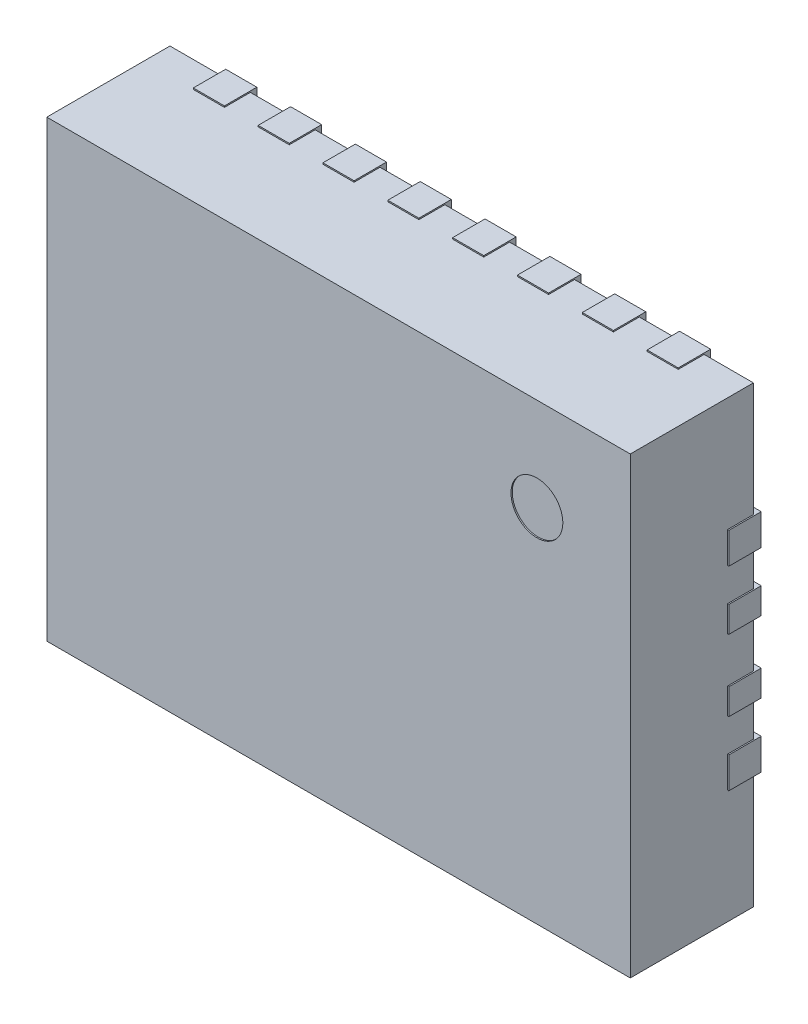
SolidWorks part; units mm, degrees
ref_plane "Front Plane" through (0, 0, 0) normal (0, 0, 1) x (1, 0, 0)
ref_plane "Top Plane" through (0, 0, 0) normal (0, 1, 0) x (1, 0, 0)
ref_plane "Right Plane" through (0, 0, 0) normal (1, 0, 0) x (0, 0, -1)
sketch "Sketch1" plane through (0, 0, 0) normal (0, 0, 1) x (1, 0, 0)
  line L1 (-2.25, 1.75) -> (2.25, 1.75)
  line L2 (-2.25, 1.75) -> (-2.25, -1.75)
  line L3 (-2.25, -1.75) -> (2.25, -1.75)
  line L4 (2.25, 1.75) -> (2.25, -1.75)
  line L5 (-2.25, 1.75) -> (2.25, -1.75) construction
  line L6 (-2.25, -1.75) -> (2.25, 1.75) construction
  point P0 (0, 0)
  dimension "D1" = 4.5
  dimension "D2" = 3.5
extrude "Boss-Extrude1" add sketch "Sketch1" along normal blind 0.95 contours L4 L3 L2 L1
sketch "Sketch2" plane through (0, 0, 0.95) normal (0, 0, 1) x (1, 0, 0)
  line L0 (1.53, 1.03) -> (1.53, 1.75) construction
  line L1 (-2.25, 1.75) -> (2.25, 1.75) construction
  line L2 (1.53, 1.03) -> (2.25, 1.03) construction
  line L4 (2.25, 1.75) -> (2.25, -1.75) construction
  circle A0 centre (1.53, 1.03) radius 0.2
  dimension "D1" = 0.4
  dimension "D2" = 0.72
extrude "Cut-Extrude1" cut sketch "Sketch2" against normal blind 0.01
sketch "Sketch3" plane through (0, 0, 0) normal (0, 0, -1) x (-1, 0, 0)
  line L0 (1.525, 0.375) -> (2.26, 0.375)
  line L1 (1.4995, -1.025) -> (-1.4995, -1.025)
  line L2 (1.525, -0.9995) -> (1.525, -0.375)
  line L3 (1.4995, 1.025) -> (-1.4995, 1.025)
  line L4 (-1.525, -0.9995) -> (-1.525, -0.375)
  line L5 (1.525, -1.025) -> (-1.525, 1.025) construction
  line L6 (1.525, 1.025) -> (-1.525, -1.025) construction
  line L7 (2.25, 1.75) -> (2.25, -1.75) construction
  line L8 (2.26, 0.375) -> (2.26, 0.175)
  line L9 (2.26, 0.175) -> (1.87, 0.175)
  line L10 (1.87, 0.175) -> (1.87, -0.175)
  line L11 (1.87, -0.175) -> (2.26, -0.175)
  line L12 (2.26, -0.175) -> (2.26, -0.375)
  line L13 (2.26, -0.375) -> (1.525, -0.375)
  line L14 (1.525, 0.375) -> (1.525, 0.9995)
  line L15 (-1.525, 0.375) -> (-2.26, 0.375)
  line L16 (-2.25, 1.75) -> (-2.25, -1.75) construction
  line L17 (-2.26, 0.375) -> (-2.26, 0.175)
  line L18 (-2.26, 0.175) -> (-1.87, 0.175)
  line L19 (-1.87, 0.175) -> (-1.87, -0.175)
  line L20 (-1.87, -0.175) -> (-2.26, -0.175)
  line L21 (-2.26, -0.175) -> (-2.26, -0.375)
  line L22 (-2.26, -0.375) -> (-1.525, -0.375)
  line L23 (-1.525, 0.375) -> (-1.525, 0.9995)
  line L24 (-1.175, 1.025) -> (-1.525, 0.675)
  arc A0 (-1.4995, -1.025) -> (-1.525, -0.9995) centre (-1.4995, -0.9995) cw
  arc A1 (-1.4995, 1.025) -> (-1.525, 0.9995) centre (-1.4995, 0.9995) ccw
  arc A2 (1.525, 0.9995) -> (1.4995, 1.025) centre (1.4995, 0.9995) ccw
  arc A3 (1.525, -0.9995) -> (1.4995, -1.025) centre (1.4995, -0.9995) cw
  point P0 (0, 0)
  point P28 (1.87, 0)
  point P30 (2.26, -0.275)
  point P31 (2.26, 0.275)
  point P41 (-1.87, 0)
  line M2 (-2.25, 1.75) -> (-2.25, -1.75)
  line M4 (2.25, -1.75) -> (2.25, 1.75)
  dimension "D3" = 0.0255
  dimension "D1" = 3.05
  dimension "D2" = 2.05
  dimension "D4" = 0.2
  dimension "D5" = 0.55
  dimension "D6" = 0.38
  dimension "D7" = 0.2
  dimension "D8" = 0.38
  dimension "D9" = 45
  dimension "D10" = 0.35
  dimension "D11" = 0.01
  dimension "D12" = 0.01
extrude "Boss-Extrude2" add sketch "Sketch3" along normal blind 0.05 and the other way blind 0.2 contours A3 L2 L13 L11 L10 L9 L0 L14 A2 L3 L24 L23 L15 L18 L19 L20 L22 L4 A0 L1 M4 M2 | L9 L8 L0 M4 | L13 L12 L11 M4 | L21 L22 L20 M2 | L17 L18 L15 M2
sketch "Sketch5" plane through (0, 0, 0) normal (0, 0, -1) x (-1, 0, 0)
  line L0 (1.97, 0.87) -> (2.25, 0.87)
  line L2 (1.97, 0.63) -> (2.25, 0.63)
  line L6 (2.25, 0.87) -> (2.26, 0.87)
  line L7 (2.26, 0.87) -> (2.26, 0.63)
  line L8 (2.26, 0.63) -> (2.25, 0.63)
  line L9 (2.25, 1.75) -> (2.25, 0.375) construction
  arc A0 (1.97, 0.87) -> (1.97, 0.63) centre (1.97, 0.75) ccw
  point P8 (1.85, 0.75)
  dimension "D2" = 0.01
  dimension "D3" = 0.4
  dimension "D4" = 0.75
  dimension "D1" = 0.24
extrude "Boss-Extrude3" add sketch "Sketch5" along normal blind 0.05 and the other way blind 0.2
pattern_linear "LPattern1" count 2 spacing 1.5 along (0, -1, 0) of "Boss-Extrude3"
mirror "Mirror1" about plane through (0, 0, 0) normal (1, 0, 0) of "LPattern1", "Boss-Extrude3"
sketch "Sketch6" plane through (0, 0, 0) normal (0, 0, -1) x (-1, 0, 0)
  line L0 (-1.87, 1.76) -> (-1.63, 1.76)
  line L1 (-1.63, 1.76) -> (-1.63, 1.75)
  line L2 (2.25, 1.75) -> (-2.25, 1.75) construction
  line L3 (-1.63, 1.75) -> (-1.63, 1.47)
  line L4 (-1.87, 1.76) -> (-1.87, 1.75)
  line L5 (-1.87, 1.75) -> (-1.87, 1.47)
  arc A0 (-1.87, 1.47) -> (-1.63, 1.47) centre (-1.75, 1.47) ccw
  point P9 (-1.75, 1.35)
  dimension "D3" = 0.4
  dimension "D1" = 0.01
  dimension "D2" = 0.24
  dimension "D4" = 1.75
extrude "Boss-Extrude4" add sketch "Sketch6" along normal blind 0.05 and the other way blind 0.2
pattern_linear "LPattern2" count 8 spacing 0.5 along (-1, 0, 0) of "Boss-Extrude4"
mirror "Mirror2" about plane through (0, 0, 0) normal (0, 1, 0) of "LPattern2", "Boss-Extrude4"
equation "\"E\"= 3.5"
equation "\"D\"= 4.5"
equation "\"H\"= \"A\" + \"A1\""
equation "\"D1@Boss-Extrude1\"=\"H\""
equation "\"D2@Sketch1\"=\"E\""
equation "\"D1@Sketch1\"=\"D\""
equation "\"D2\"= 3.05"
equation "\"E2\"= 2.05"
equation "\"L\"= 0.4"
equation "\"b\"= 0.24"
equation "\"e_\"= 0.5"
equation "\"A3\"= 0.2"
equation "\"K\"= 0.2"
equation "\"A1\"= 0.05"
equation "\"D1@Sketch3\"=\"D2\""
equation "\"D2@Sketch3\"=\"E2\""
equation "\"GND_R\"= ( \"D2\" + \"E2\" ) / 2 * 0.01"
equation "\"D3@Sketch3\"=\"GND_R\""
equation "\"D1@Boss-Extrude2\"=\"A1\""
equation "\"Px\"= 8"
equation "\"Py\"= 2"
equation "\"P\"= 2 * \"Px\" + 2 * \"Py\""
equation "\"D1@Boss-Extrude3\"=\"A1\""
equation "\"D2@Boss-Extrude3\"=\"A3\""
equation "\"D3@Sketch5\"=\"L\""
equation "\"D4@Sketch5\"=(\"Py\"/2-1)*\"e_y\"+\"e_y\"/2"
equation "\"D3@LPattern1\"=\"e_y\""
equation "\"D1@LPattern1\"=\"Py\""
equation "\"D1@Sketch5\"=\"b\""
equation "\"D1@Sketch6\"=\"D2@Sketch5\""
equation "\"D2@Sketch6\"=\"b\""
equation "\"D3@Sketch6\"=\"L\""
equation "\"D4@Sketch6\"=(\"Px\"/2-1)*\"e_\"+\"e_\"/2"
equation "\"D1@Boss-Extrude4\"=\"A1\""
equation "\"D2@Boss-Extrude4\"=\"A3\""
equation "\"D3@LPattern2\"=\"e_\""
equation "\"D1@LPattern2\"=\"Px\""
equation "\"A\"= 0.9"
equation "\"D2@Sketch2\"=\"D1@Sketch2\"*1.8"
equation "\"e_y\"= 1.5"
equation "\"D7@Sketch3\"=\"D4@Sketch3\""
equation "\"D8@Sketch3\"=\"D6@Sketch3\""
equation "\"D2@Boss-Extrude2\"=\"A3\""
equation "\"D12@Sketch3\"=\"D11@Sketch3\""
